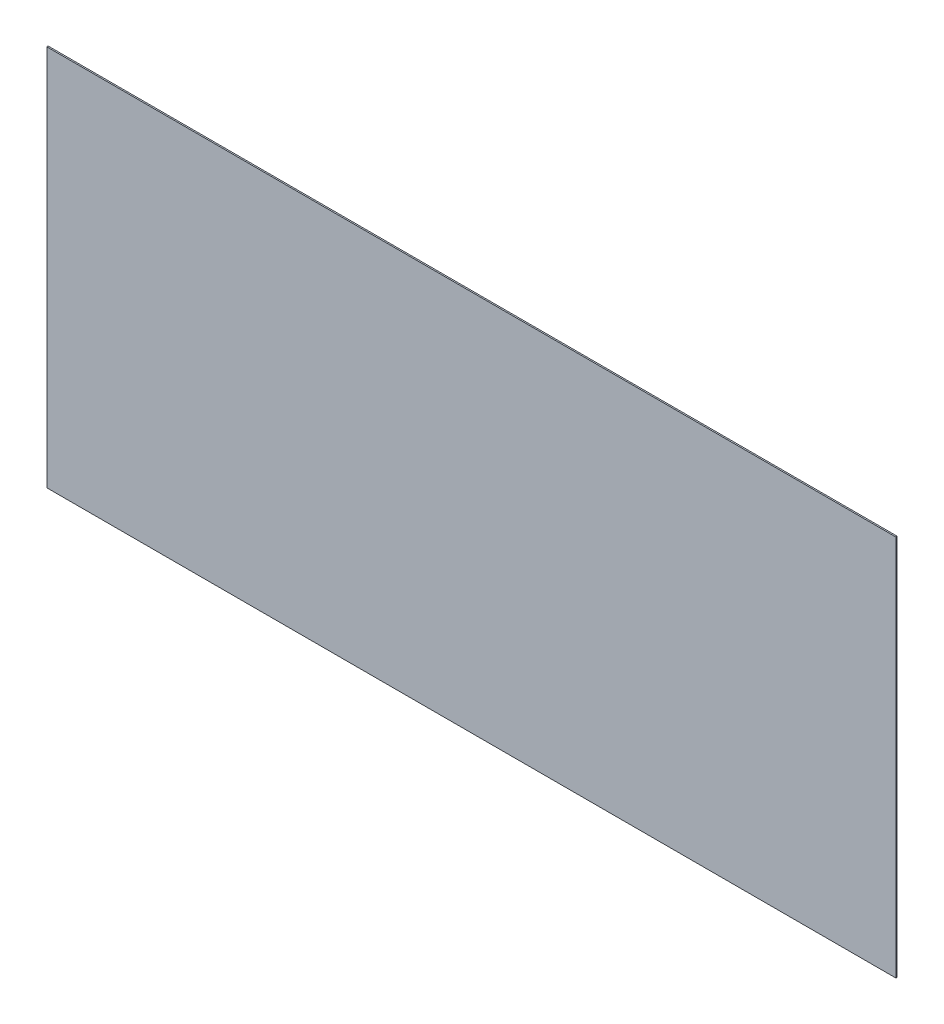
SolidWorks part; units mm, degrees
ref_plane "Front Plane" through (0, 0, 0) normal (0, 0, 1) x (1, 0, 0)
ref_plane "Top Plane" through (0, 0, 0) normal (0, 1, 0) x (1, 0, 0)
ref_plane "Right Plane" through (0, 0, 0) normal (1, 0, 0) x (0, 0, -1)
other "Configuration Table"
sketch "Sketch1" plane through (0, 0, 0) normal (0, 0, 1) x (1, 0, 0)
  line L1 (69, 406) -> (687, 406)
  line L2 (69, 406) -> (69, 684)
  line L3 (69, 684) -> (687, 684)
  line L4 (687, 406) -> (687, 684)
extrude "STORE_klape_kaset_kati_on_ic_sac_1" add sketch "Sketch1" along normal blind 1 separate body
